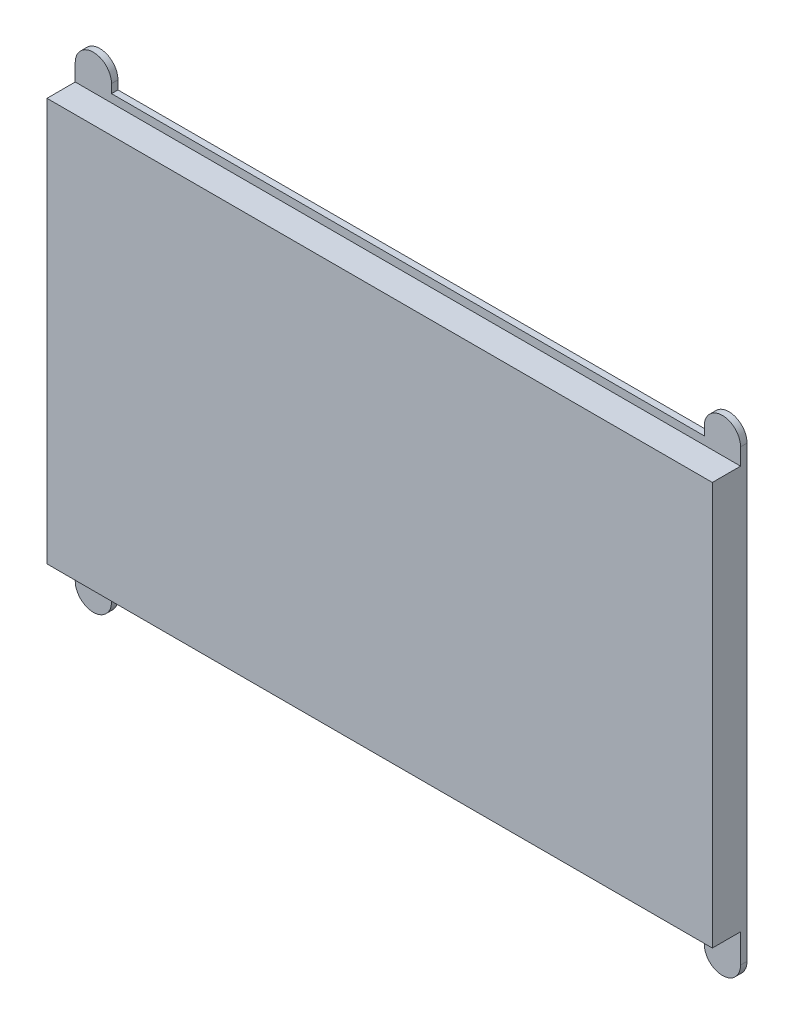
SolidWorks part; units mm, degrees
ref_plane "Plan de face" through (0, 0, 0) normal (0, 0, 1) x (1, 0, 0)
ref_plane "Plan de dessus" through (0, 0, 0) normal (0, 1, 0) x (1, 0, 0)
ref_plane "Plan de droite" through (0, 0, 0) normal (1, 0, 0) x (0, 0, -1)
sketch "Esquisse1" plane through (0, 0, 0) normal (0, 0, 1) x (1, 0, 0)
  line L0 (-82.5, 53.5) -> (-82.5, 55.65)
  line L1 (-73.5, 53.5) -> (73.5, 53.5)
  line L2 (-82.5, 53.5) -> (-82.5, -53.5)
  line L4 (82.5, 53.5) -> (82.5, -53.5)
  line L5 (73.5, 53.5) -> (73.5, 55.65)
  line L6 (-73.5, 55.65) -> (-73.5, 53.5)
  line L7 (82.5, 55.65) -> (82.5, 53.5)
  line L8 (-82.5, -53.5) -> (-82.5, -55.65)
  line L10 (-73.5, -55.65) -> (-73.5, -53.5)
  line L11 (-73.5, -53.5) -> (73.5, -53.5)
  line L12 (73.5, -53.5) -> (73.5, -55.65)
  line L14 (82.5, -55.65) -> (82.5, -53.5)
  arc A0 (-82.5, 55.65) -> (-73.5, 55.65) centre (-78, 55.65) cw
  arc A1 (73.5, 55.65) -> (82.5, 55.65) centre (78, 55.65) cw
  arc A2 (-82.5, -55.65) -> (-73.5, -55.65) centre (-78, -55.65) ccw
  arc A3 (73.5, -55.65) -> (82.5, -55.65) centre (78, -55.65) ccw
  point P20 (82.5, 0)
  point P21 (0, 53.5)
  dimension "D3" = 4.5
  dimension "D1" = 165
  dimension "D2" = 2.15
  dimension "D4" = 107
extrude "Boss.-Extru.1" add sketch "Esquisse1" along normal blind 1.6
sketch "Esquisse2" plane through (0, 0, 1.6) normal (0, 0, 1) x (1, 0, 0)
  line L0 (-82.5, 55.65) -> (-82.5, -55.65) construction
  line L1 (-82.5, 51.5) -> (82.5, 51.5)
  line L2 (-82.5, 51.5) -> (-82.5, -48.5)
  line L3 (-82.5, -48.5) -> (82.5, -48.5)
  line L4 (82.5, 51.5) -> (82.5, -48.5)
  line L5 (82.5, -55.65) -> (82.5, 55.65) construction
  line L6 (73.5, 53.5) -> (-73.5, 53.5) construction
  dimension "D1" = 100
  dimension "D2" = 2
extrude "Boss.-Extru.2" add sketch "Esquisse2" along normal blind 7
